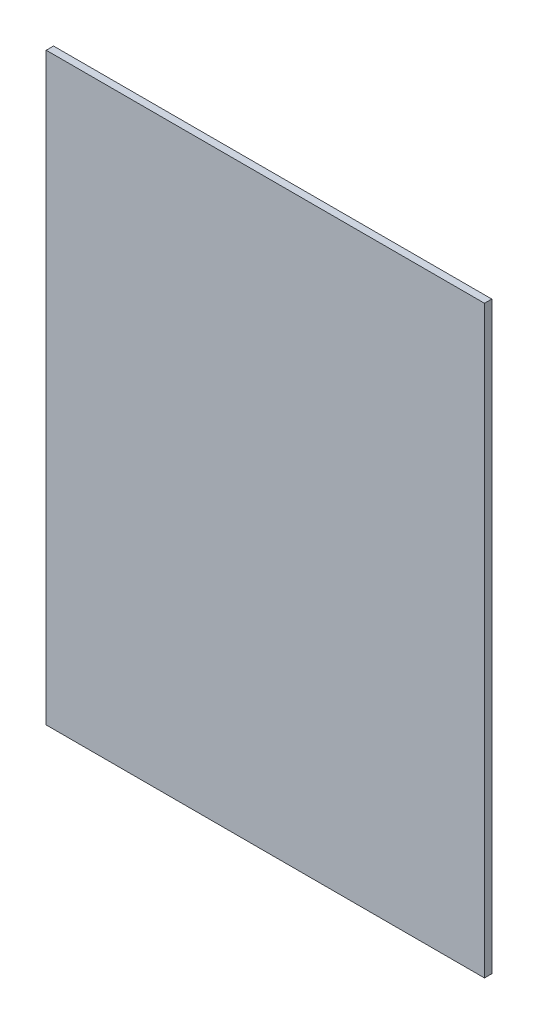
SolidWorks part; units mm, degrees
material "Glass"
ref_plane "Front Plane" through (0, 0, 0) normal (0, 0, 1) x (1, 0, 0)
ref_plane "Top Plane" through (0, 0, 0) normal (0, 1, 0) x (1, 0, 0)
ref_plane "Right Plane" through (0, 0, 0) normal (1, 0, 0) x (0, 0, -1)
sketch "Sketch1" plane through (0, 0, 0) normal (0, 0, 1) x (1, 0, 0)
  line L1 (0, 0) -> (152.4, 0)
  line L2 (0, 0) -> (0, 203.2)
  line L3 (0, 203.2) -> (152.4, 203.2)
  line L4 (152.4, 0) -> (152.4, 203.2)
  dimension "D1" = 152.4
  dimension "D2" = 203.2
extrude "Boss-Extrude1" add sketch "Sketch1" along normal blind 2.54
